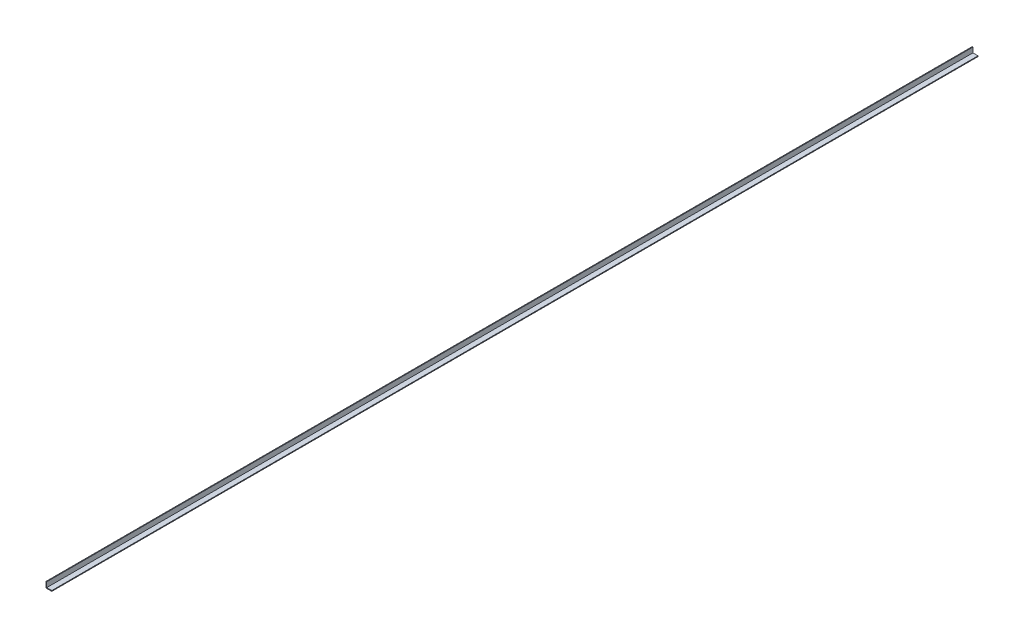
SolidWorks part; units mm, degrees
material "ASTM A36 Acero"
ref_plane "Alzado" through (0, 0, 0) normal (0, 0, 1) x (1, 0, 0)
ref_plane "Planta" through (0, 0, 0) normal (0, 1, 0) x (1, 0, 0)
ref_plane "Vista lateral" through (0, 0, 0) normal (1, 0, 0) x (0, 0, -1)
sketch "Croquis1" plane through (0, 0, 0) normal (0, 0, 1) x (1, 0, 0)
  line L0 (0, 38.1) -> (0, 0)
  line L1 (0, 0) -> (38.1, 0)
  line L2 (38.1, 0) -> (38.1, 4.76)
  line L3 (38.1, 4.76) -> (4.76, 4.76)
  line L4 (4.76, 4.76) -> (4.76, 38.1)
  line L5 (4.76, 38.1) -> (0, 38.1)
  dimension "D1" = 4.76
  dimension "D2" = 38.1
extrude "Saliente-Extruir1" add sketch "Croquis1" against normal blind 6100
